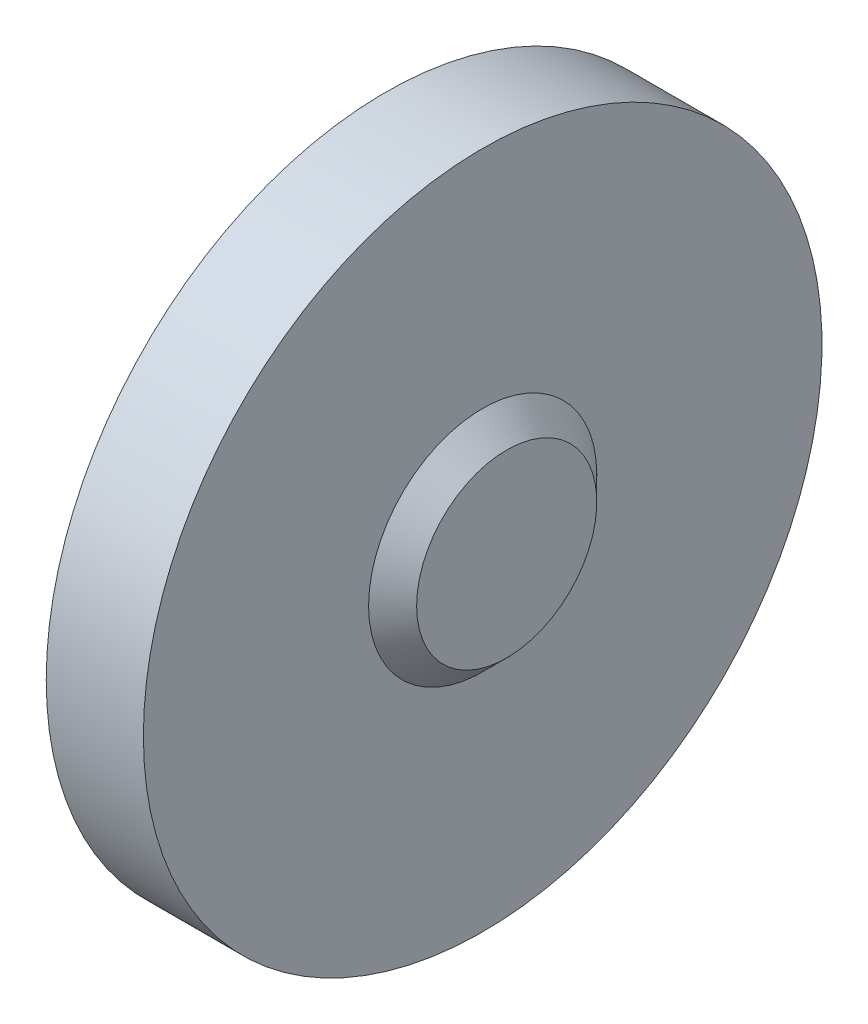
SolidWorks part; units mm, degrees
ref_plane "Alzado" through (0, 0, 0) normal (0, 0, 1) x (1, 0, 0)
ref_plane "Planta" through (0, 0, 0) normal (0, 1, 0) x (1, 0, 0)
ref_plane "Vista lateral" through (0, 0, 0) normal (1, 0, 0) x (0, 0, -1)
sketch "Croquis1" plane through (0, 0, 0) normal (0, 0, 1) x (1, 0, 0)
  line L0 (-1.9823, 9.4159) -> (-1.9823, 28)
  line L1 (-1.9823, 28) -> (-10, 28)
  line L2 (-10, 28) -> (-10, 21.3097)
  line L3 (-10, 21.3097) -> (-5, 21.3097)
  line L4 (-5, 21.3097) -> (-5, 7.4336)
  line L5 (-5, 7.4336) -> (-12, 7.4336)
  line L6 (-12, 7.4336) -> (-12, 0)
  line L8 (-1.9823, 9.4159) -> (0, 7.4336)
  line L9 (0, 7.4336) -> (0, 0)
  line L11 (-12, 0) -> (0, 0)
  dimension "D2" = 12
  dimension "D3" = 10
  dimension "D4" = 5
revolve "Revolución2" add sketch "Croquis1" angle 360 about L11
